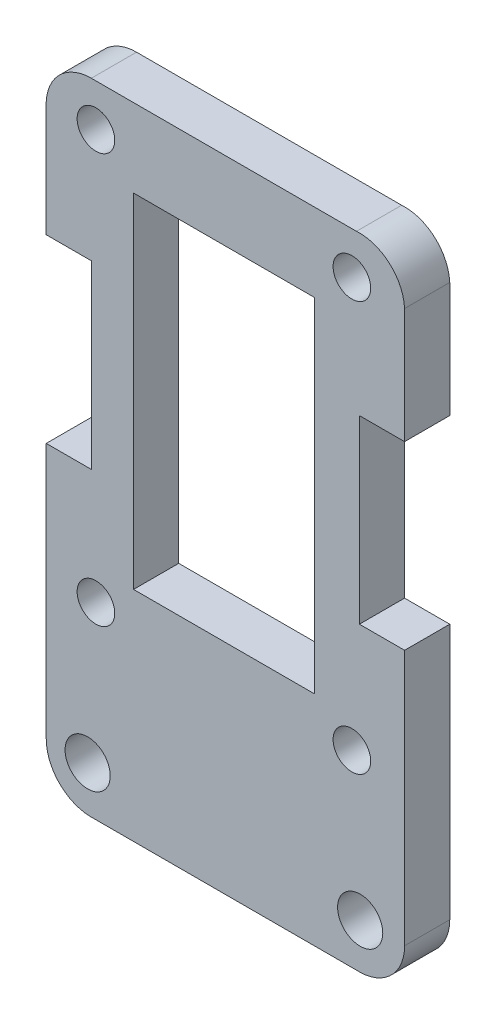
SolidWorks part; units mm, degrees
ref_plane "前基準面" through (0, 0, 0) normal (0, 0, 1) x (1, 0, 0)
ref_plane "上基準面" through (0, 0, 0) normal (0, 1, 0) x (1, 0, 0)
ref_plane "右基準面" through (0, 0, 0) normal (1, 0, 0) x (0, 0, -1)
sketch "草圖1" plane through (0, 0, 0) normal (0, 0, 1) x (1, 0, 0)
  line L0 (206.7978, 102.4859) -> (218.7988, 102.4859) construction
  line L1 (206.7978, 125.2859) -> (206.7978, 102.4859) construction
  line L2 (218.7988, 125.2859) -> (206.7978, 125.2859) construction
  line L3 (218.7988, 102.4859) -> (218.7988, 125.2859) construction
  line L4 (224.7994, 107.9859) -> (221.7994, 107.9859) construction
  line L5 (221.7994, 107.9859) -> (221.7994, 119.9859) construction
  line L6 (203.9977, 107.9859) -> (200.9975, 107.9859) construction
  line L7 (203.9977, 119.9859) -> (203.9977, 107.9859) construction
  line L8 (200.9975, 119.9859) -> (203.9977, 119.9859) construction
  line L9 (200.9975, 127.6446) -> (200.9975, 119.9859) construction
  line L10 (206.7978, 102.4859) -> (218.7988, 102.4859)
  line L11 (206.7978, 125.2859) -> (206.7978, 102.4859)
  line L12 (218.7988, 125.2859) -> (206.7978, 125.2859)
  line L13 (218.7988, 102.4859) -> (218.7988, 125.2859)
  line L14 (224.7994, 107.9859) -> (221.7994, 107.9859)
  line L15 (221.7994, 107.9859) -> (221.7994, 119.9859)
  line L16 (203.9977, 107.9859) -> (200.9975, 107.9859)
  line L17 (203.9977, 119.9859) -> (203.9977, 107.9859)
  line L18 (200.9975, 119.9859) -> (203.9977, 119.9859)
  line L19 (200.9975, 127.6446) -> (200.9975, 119.9859)
  line L20 (200.9975, 107.9859) -> (200.9975, 90.9845)
  line L21 (224.7994, 107.9859) -> (224.7994, 90.988)
  line L22 (203.8978, 87.9859) -> (221.7994, 87.988)
  line L23 (203.9935, 130.4877) -> (221.6031, 130.4877)
  line L24 (221.7994, 119.9859) -> (224.7994, 119.9859)
  line L25 (224.7994, 119.9859) -> (224.7994, 127.6451)
  arc A0 (200.9975, 90.9845) -> (203.8978, 87.9859) centre (203.9978, 90.9846) ccw construction
  arc A1 (221.7994, 87.988) -> (224.7994, 90.988) centre (221.7991, 90.9882) ccw construction
  arc A2 (224.7994, 127.6451) -> (221.6031, 130.4877) centre (221.8031, 127.4942) ccw construction
  circle A3 centre (204.298, 127.688) radius 1.25 construction
  circle A4 centre (221.2993, 127.688) radius 1.25 construction
  circle A5 centre (221.2993, 100.4858) radius 1.25 construction
  circle A6 centre (221.8495, 90.9851) radius 1.5 construction
  circle A7 centre (203.748, 90.9851) radius 1.5 construction
  circle A8 centre (204.298, 100.4858) radius 1.25 construction
  arc A9 (203.9935, 130.4877) -> (200.9975, 127.6446) centre (203.9935, 127.4876) ccw construction
  arc A10 (200.9975, 90.9845) -> (203.8978, 87.9859) centre (203.9978, 90.9846) ccw
  arc A11 (221.7994, 87.988) -> (224.7994, 90.988) centre (221.7991, 90.9882) ccw
  arc A12 (224.7994, 127.6451) -> (221.6031, 130.4877) centre (221.8031, 127.4942) ccw
  circle A13 centre (204.298, 127.688) radius 1.25
  circle A14 centre (221.2993, 127.688) radius 1.25
  circle A15 centre (221.2993, 100.4858) radius 1.25
  circle A16 centre (221.8495, 90.9851) radius 1.5
  circle A17 centre (203.748, 90.9851) radius 1.5
  circle A18 centre (204.298, 100.4858) radius 1.25
  arc A19 (203.9935, 130.4877) -> (200.9975, 127.6446) centre (203.9935, 127.4876) ccw
extrude "填料-伸長1" add sketch "草圖1" along normal blind 3
